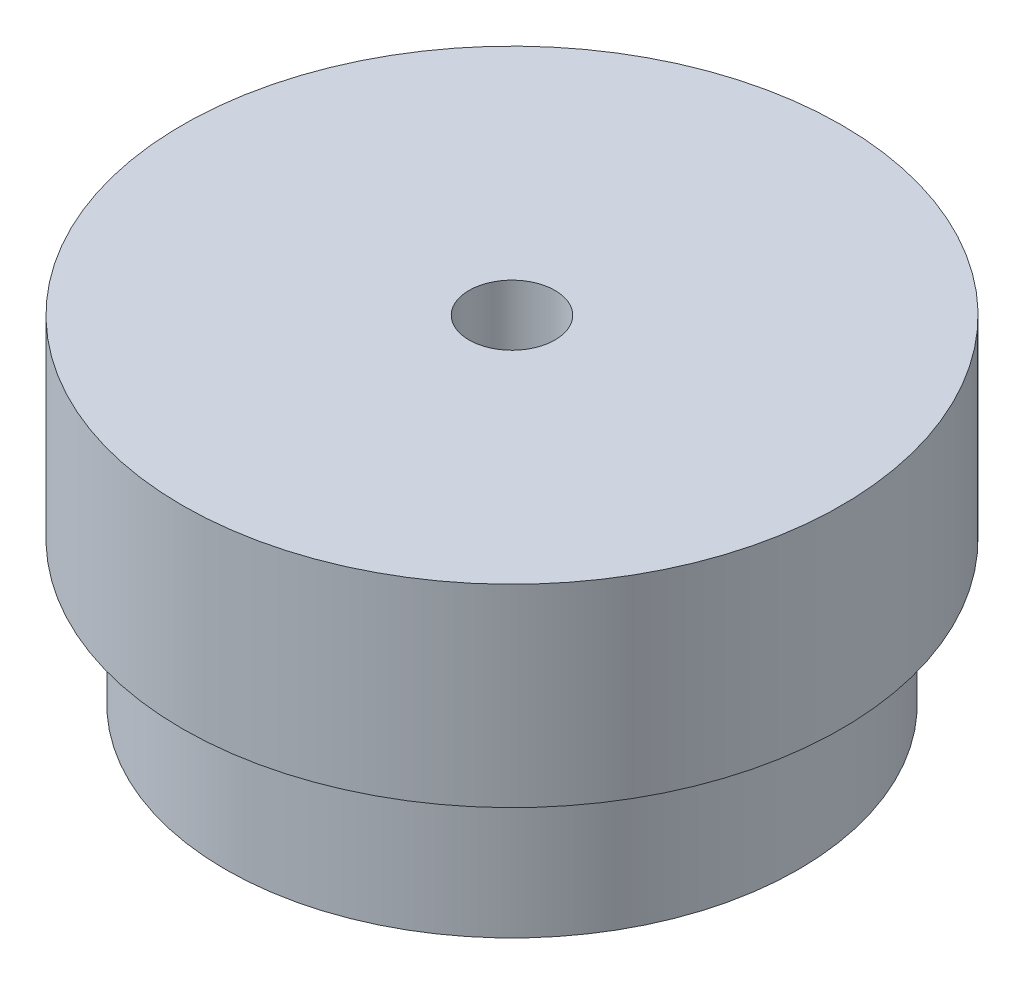
SolidWorks part; units mm, degrees
ref_plane "Спереди" through (0, 0, 0) normal (0, 0, 1) x (1, 0, 0)
ref_plane "Сверху" through (0, 0, 0) normal (0, 1, 0) x (1, 0, 0)
ref_plane "Справа" through (0, 0, 0) normal (1, 0, 0) x (0, 0, -1)
sketch "Эскиз1" plane through (0, 0, 0) normal (1, 0, 0) x (0, 0, -1)
  line L0 (0, 0) -> (0, 25008.0836) construction
  line L1 (1.5, 0) -> (11.5, 0) construction
  line L2 (11.5, 0) -> (11.5, -1.75)
  line L3 (11.5, -1.75) -> (10, -1.75)
  line L4 (10, -1.75) -> (10, -6.75)
  line L5 (10, -6.75) -> (7.5, -6.75)
  line L6 (7.5, -6.75) -> (7.5, -8.25)
  line L7 (7.5, -8.25) -> (1.5, -8.25)
  line L8 (1.5, -8.25) -> (1.5, 0)
  line L9 (11.5, 0) -> (11.5, 5)
  line L10 (11.5, 5) -> (1.5, 5)
  line L11 (1.5, 5) -> (1.5, 0)
  dimension "D1" = 3
  dimension "D2" = 23
  dimension "D3" = 20
  dimension "D4" = 15
  dimension "D5" = 1.5
  dimension "D6" = 1.75
  dimension "D7" = 6.75
  dimension "D8" = 5
revolve "Повернуть1" add sketch "Эскиз1" angle 360 about L0
